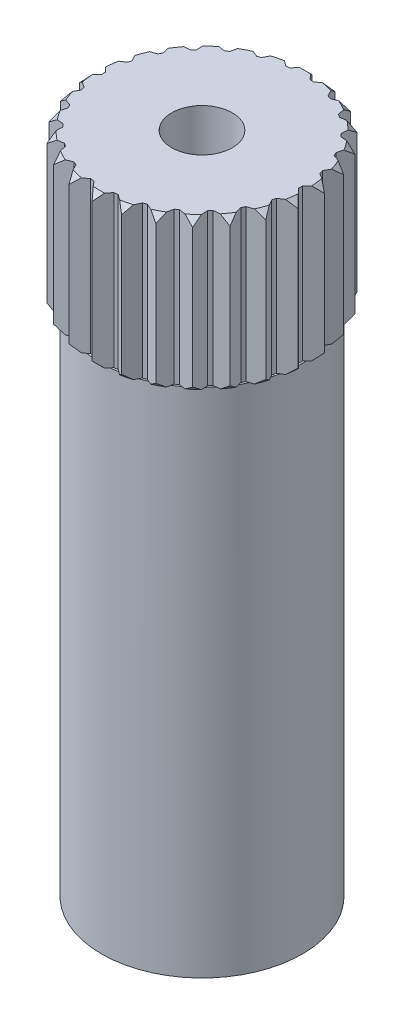
SolidWorks part; units mm, degrees
material "Brass"
ref_plane "Front Plane" through (0, 0, 0) normal (0, 0, 1) x (1, 0, 0)
ref_plane "Top Plane" through (0, 0, 0) normal (0, 1, 0) x (1, 0, 0)
ref_plane "Right Plane" through (0, 0, 0) normal (1, 0, 0) x (0, 0, -1)
sketch "Sketch12" plane through (0, 0, 0) normal (0, 1, 0) x (1, 0, 0)
  circle A0 centre (0, 0) radius 2.9
  dimension "D1" = 5.8
extrude "Boss-Extrude4" add sketch "Sketch12" along normal blind 13.5 separate body
sketch "Sketch13" plane through (0, 13.5, 0) normal (0, 1, 0) x (1, 0, 0)
  circle A2 centre (0, 0) radius 2.6
  circle A3 centre (0, 0) radius 2.9 construction
  dimension "D1" = 0.3
extrude "Boss-Extrude5" add sketch "Sketch13" along normal blind 4
sketch "Sketch14" plane through (0, 17.5, 0) normal (0, 1, 0) x (1, 0, 0)
  line L0 (0, 2.6) -> (0, 2.9) construction
  line L1 (0, 2.9) -> (-0.2629, 2.5867)
  line L2 (0, 2.9) -> (0.2629, 2.5867)
  line L3 (-0.2629, 2.5867) -> (0.2629, 2.5867) construction
  circle A0 centre (0, 0) radius 2.9 construction
  circle A1 centre (0, 0) radius 2.6
  arc A2 (0.2629, 2.5867) -> (-0.2629, 2.5867) centre (0, 0) ccw
  dimension "D2" = 80
  dimension "D3" = 0.5258
  dimension "D4" = 0.3
  dimension "D1" = 0
extrude "Boss-Extrude6" add sketch "Sketch14" against normal up to body separate body
pattern_circular "CirPattern1" count 26 over 360 about axis through (0, 0, 0) along (0, 1, 0) of "Boss-Extrude6"
sketch "Sketch15" plane through (0, 0, 0) normal (1, 0, 0) x (0, 0, -1)
  line L0 (2.9, 17.3232) -> (2.9, 17.5)
  line L1 (2.9, 13.5) -> (2.9, 17.5) construction
  line L2 (2.9, 17.5) -> (2.7232, 17.5)
  line L3 (2.1682, 17.5) -> (2.5678, 17.5) construction
  line L4 (2.7232, 17.5) -> (2.9, 17.3232)
  dimension "D1" = 45
  dimension "D2" = 0.25
revolve "Cut-Revolve1" cut sketch "Sketch15" angle 360 about axis through (0, 17.5, 0) along (0, -1, 0)
sketch "Sketch16" plane through (0, 17.5, 0) normal (0, 1, 0) x (1, 0, 0)
  circle A0 centre (0, 0) radius 0.8
  dimension "D1" = 1.6
extrude "Cut-Extrude1" cut sketch "Sketch16" against normal blind 4
ref_plane "Plane1" through (-0.3638, 13.5, -2.5744) normal (-0.9902, 0, 0.1399) x (0.1399, 0, 0.9902)
sketch "Sketch17" plane through (0, 0, 0) normal (0, 0, 1) x (1, 0, 0)
  line L0 (2.9, 0) -> (2.65, 0)
  line L1 (-2.9, 0) -> (2.9, 0) construction
  line L2 (2.65, 0) -> (2.65, 13.5)
  line L3 (2.65, 13.5) -> (2.9, 13.5)
  line L4 (2.9, 13.5) -> (2.9, 0)
  line L5 (0, 0) -> (2.65, 0) construction
  line L6 (2.7115, 13.5) -> (2.3254, 13.5) construction
  dimension "D1" = 0.25
  dimension "D2" = 2.65
  dimension "D3" = 2.9
revolve "Cut-Revolve2" cut sketch "Sketch17" angle 360 about axis through (0, 13.5, 0) along (0, -1, 0)
ref_plane "Plane2" through (0, 15.5, 0) normal (0, 1, 0) x (1, 0, 0)
mirror "Mirror1" about plane through (0, 15.5, 0) normal (0, 1, 0) of "Cut-Revolve1"
